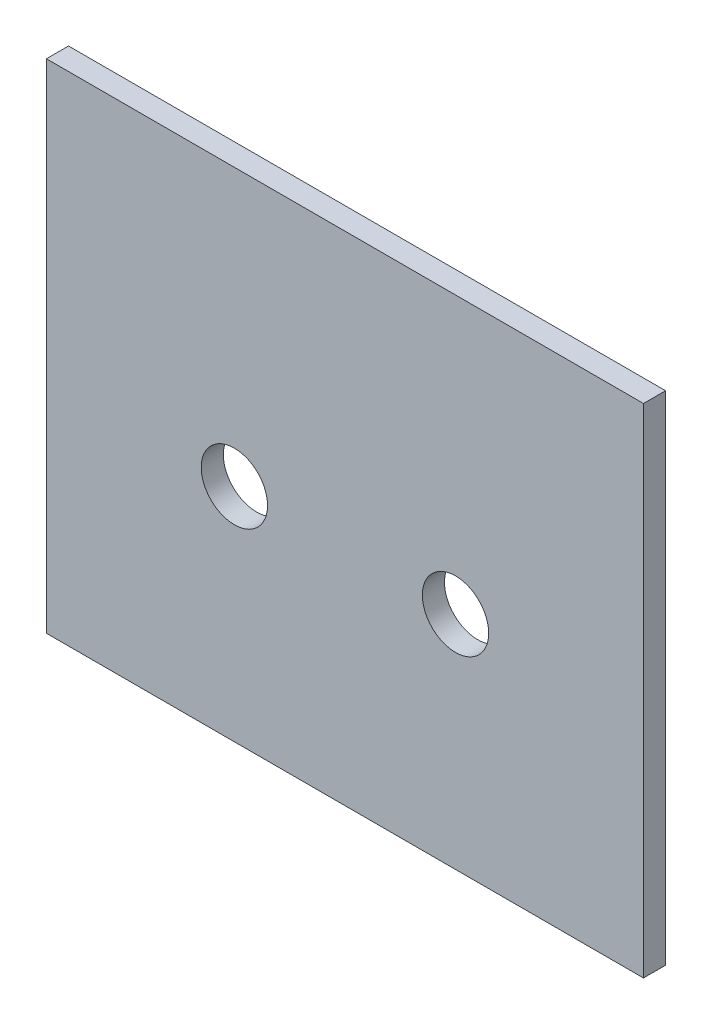
SolidWorks part; units mm, degrees
material "A286 Iron Base Superalloy"
ref_plane "Front Plane" through (0, 0, 0) normal (0, 0, 1) x (1, 0, 0)
ref_plane "Top Plane" through (0, 0, 0) normal (0, 1, 0) x (1, 0, 0)
ref_plane "Right Plane" through (0, 0, 0) normal (1, 0, 0) x (0, 0, -1)
sketch "Sketch1" plane through (0, 0, 0) normal (0, 0, 1) x (1, 0, 0)
  line L1 (0, 0) -> (270, 0)
  line L2 (0, 0) -> (0, 225)
  line L3 (0, 225) -> (270, 225)
  line L4 (270, 0) -> (270, 225)
  line L5 (0, 175) -> (0, 100)
  line L6 (0, 100) -> (270, 100) construction
  circle A0 centre (85, 100) radius 15
  circle A1 centre (185, 100) radius 15
  point P12 (0, 0)
  dimension "D6" = 85
  dimension "D7" = 30
  dimension "D8" = 30
  dimension "D1" = 270
  dimension "D2" = 225
  dimension "D3" = 50
  dimension "D4" = 75
  dimension "D5" = 85
extrude "Boss-Extrude1" add sketch "Sketch1" against normal blind 10 contours L2 L6 A0 A1 L4 L3 | L6 L2 L1 L4 A1 A0
